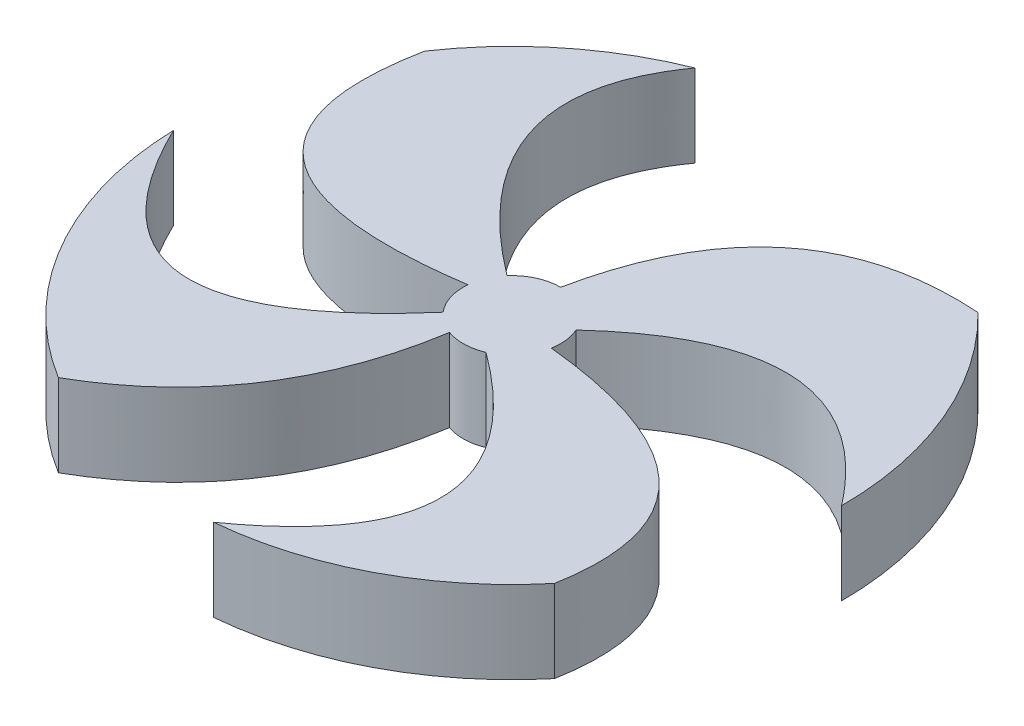
SolidWorks part; units mm, degrees
ref_plane "Front Plane" through (0, 0, 0) normal (0, 0, 1) x (1, 0, 0)
ref_plane "Top Plane" through (0, 0, 0) normal (0, 1, 0) x (1, 0, 0)
ref_plane "Right Plane" through (0, 0, 0) normal (1, 0, 0) x (0, 0, -1)
sketch "Sketch3" plane through (0, 0, 0) normal (0, 1, 0) x (1, 0, 0)
  arc A0 (-2.9467, 0.2782) -> (-2.2559, -1.916) centre (0, 0) ccw
  arc A1 (-7.4488, 18.55) -> (-16.5288, 11.2422) centre (0, 0) ccw
  arc A2 (19.9897, 0) -> (13.9799, 14.2882) centre (0, 0) ccw
  arc A3 (1.8159, -19.9071) -> (15.3666, -12.785) centre (0, 0) ccw
  arc A4 (-19.9821, -0.5497) -> (-10.4873, -17.0178) centre (0, 0) ccw
  arc A5 (0, 2.9598) -> (-2.2362, 1.939) centre (0, 0) ccw
  arc A6 (2.9132, -0.5229) -> (2.7127, 1.184) centre (0, 0) ccw
  arc A7 (-1.0002, -2.7857) -> (1.1567, -2.7244) centre (0, 0) ccw
  spline S0 degree 2 poles (0, 2.9598) (2.4745, 15.0759) (13.9799, 14.2882) knots 0 0 0 1 1 1
  spline S1 degree 2 poles (-2.2362, 1.939) (-13.3595, 10.3407) (-7.4488, 18.55) knots 0 0 0 1 1 1
  spline S2 degree 2 poles (2.7127, 1.184) (12.2957, 10.0089) (19.9897, 0) knots 0 0 0 1 1 1
  spline S3 degree 2 poles (2.9132, -0.5229) (17.3177, -1.9467) (15.3666, -12.785) knots 0 0 0 1 1 1
  spline S4 degree 2 poles (1.1567, -2.7244) (13.3512, -11.7112) (1.8159, -19.9071) knots 0 0 0 1 1 1
  spline S5 degree 2 poles (-1.0002, -2.7857) (-2.5468, -12.4902) (-10.4873, -17.0178) knots 0 0 0 1 1 1
  spline S6 degree 2 poles (-2.2559, -1.916) (-13.1713, -14.5048) (-19.9821, -0.5497) knots 0 0 0 1 1 1
  spline S7 degree 2 poles (-2.9467, 0.2782) (-19.1308, -2.127) (-16.5288, 11.2422) knots 0 0 0 1 1 1
extrude "Boss-Extrude2" add sketch "Sketch3" along normal blind 5
